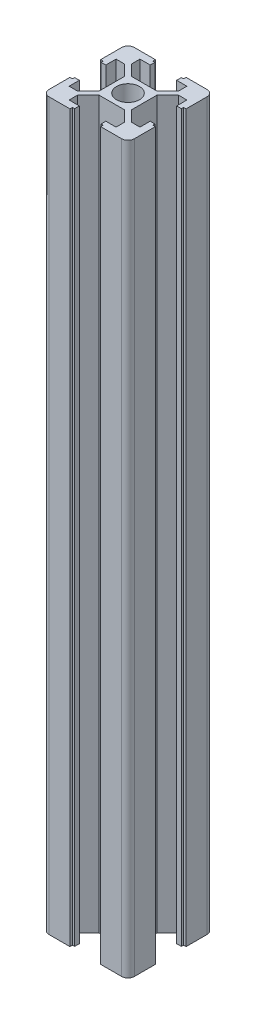
SolidWorks part; units mm, degrees
material "氧化铝"
ref_plane "前视基准面" through (0, 0, 0) normal (0, 0, 1) x (1, 0, 0)
ref_plane "上视基准面" through (0, 0, 0) normal (0, 1, 0) x (1, 0, 0)
ref_plane "右视基准面" through (0, 0, 0) normal (1, 0, 0) x (0, 0, -1)
sketch "草图1" plane through (0, 0, 0) normal (0, 1, 0) x (1, 0, 0)
  line L1 (-10, 10) -> (10, 10)
  line L2 (-10, 10) -> (-10, -10)
  line L3 (-10, -10) -> (10, -10)
  line L4 (10, 10) -> (10, -10)
  line L5 (-10, 10) -> (10, -10) construction
  line L6 (-10, -10) -> (10, 10) construction
  point P0 (0, 0)
  dimension "D1" = 20
  dimension "D2" = 20
extrude "凸台-拉伸1" add sketch "草图1" along normal mid plane 170
sketch "草图4" plane through (0, 85, 0) normal (0, 1, 0) x (1, 0, 0)
  circle A0 centre (0, 0) radius 2.7
  dimension "D1" = 5.4
extrude "切除-拉伸3" cut sketch "草图4" against normal blind 9999
sketch "草图2" plane through (0, 85, 0) normal (0, 1, 0) x (1, 0, 0)
  line L0 (10, 10) -> (-10, 10) construction
  line L1 (-3.6, 10.6) -> (3.6, 10.6)
  line L2 (-3.6, 10.6) -> (-3.6, 9.4)
  line L3 (-3.6, 9.4) -> (3.6, 9.4)
  line L4 (3.6, 10.6) -> (3.6, 9.4)
  line L5 (-3.6, 10.6) -> (3.6, 9.4) construction
  line L6 (-3.6, 9.4) -> (3.6, 10.6) construction
  line L8 (-3.1, 11.7) -> (3.1, 11.7)
  line L9 (-3.1, 11.7) -> (-3.1, 8.3)
  line L10 (-3.1, 8.3) -> (3.1, 8.3)
  line L11 (3.1, 11.7) -> (3.1, 8.3)
  line L12 (-3.1, 11.7) -> (3.1, 8.3) construction
  line L13 (-3.1, 8.3) -> (3.1, 11.7) construction
  point P0 (0, 10)
  point P7 (0, 10)
  dimension "D1" = 1.2
  dimension "D2" = 3.4
  dimension "D3" = 7.2
  dimension "D4" = 6.2
extrude "切除-拉伸1" cut sketch "草图2" against normal blind 9999 contours L2 L3 L4 L1 | L10 L11 L8 L9
sketch "草图3" plane through (0, 85, 0) normal (0, 1, 0) x (1, 0, 0)
  line L5 (5.5, 8.3) -> (-5.5, 8.3)
  line L6 (-3.1, 8.3) -> (3.1, 8.3) construction
  line L7 (-5.5, 8.3) -> (-5.5, 6.3)
  line L8 (-3, 3.8) -> (3, 3.8)
  line L9 (0, 3.8) -> (0, 8.3) construction
  line L12 (-5.5, 6.3) -> (-3, 3.8)
  line L13 (5.5, 6.3) -> (3, 3.8)
  line L14 (5.5, 8.3) -> (5.5, 6.3)
  dimension "D1" = 5.5
  dimension "D2" = 4.5
  dimension "D3" = 2
  dimension "D4" = 3
extrude "切除-拉伸2" cut sketch "草图3" against normal blind 9999
pattern_circular "阵列(圆周)5" count 4 over 360 about axis through (0, 0, 0) along (0, 1, 0) of "切除-拉伸1", "切除-拉伸2"
fillet "圆角1" radius 1.5 4 edges at (-10, 0, 10) (10, 0, 10) (-10, 0, -10) (10, 0, -10)
